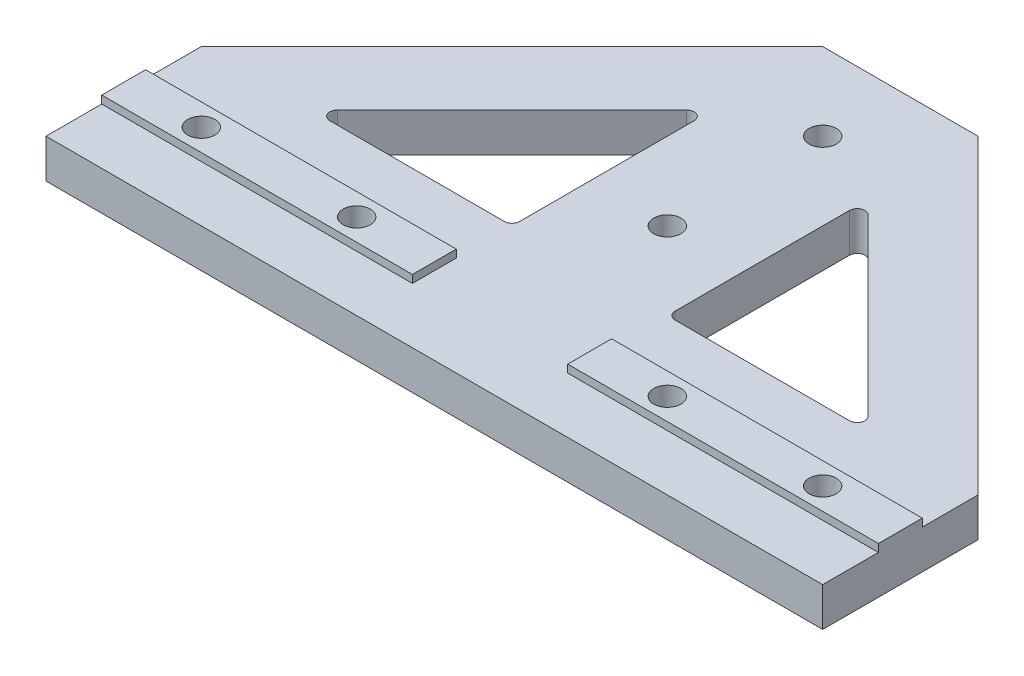
SolidWorks part; units mm, degrees
ref_plane "Plano frontal" through (0, 0, 0) normal (0, 0, 1) x (1, 0, 0)
ref_plane "Plano superior" through (0, 0, 0) normal (0, 1, 0) x (1, 0, 0)
ref_plane "Plano direito" through (0, 0, 0) normal (1, 0, 0) x (0, 0, -1)
sketch "Esboço1" plane through (0, 0, 0) normal (0, 1, 0) x (1, 0, 0)
  line L0 (-50, 0) -> (-50, 20)
  line L1 (-10, 60) -> (10, 60)
  line L2 (10, 60) -> (50, 20)
  line L3 (50, 20) -> (50, 0)
  line L4 (50, 0) -> (-50, 0)
  line L5 (-10, 43.4437) -> (-10, 21)
  line L6 (-33.4437, 20) -> (-11, 20)
  line L7 (-11.7071, 44.1508) -> (-34.1508, 21.7071)
  line L8 (0, 60) -> (0, 0) construction
  line L9 (-50, 10) -> (50, 10) construction
  line L10 (-10, 60) -> (-50, 20)
  line L11 (11.7071, 44.1508) -> (34.1508, 21.7071)
  line L12 (33.4437, 20) -> (11, 20)
  line L13 (10, 43.4437) -> (10, 21)
  arc A0 (-10, 21) -> (-11, 20) centre (-11, 21) cw
  arc A1 (-33.4437, 20) -> (-34.1508, 21.7071) centre (-33.4437, 21) cw
  arc A2 (-11.7071, 44.1508) -> (-10, 43.4437) centre (-11, 43.4437) cw
  circle A3 centre (-40, 10) radius 1.75
  circle A4 centre (-20, 10) radius 1.75
  circle A5 centre (0, 50) radius 1.75
  circle A6 centre (0, 30) radius 1.75
  circle A7 centre (20, 10) radius 1.75
  circle A8 centre (40, 10) radius 1.75
  arc A9 (11.7071, 44.1508) -> (10, 43.4437) centre (11, 43.4437) ccw
  arc A10 (33.4437, 20) -> (34.1508, 21.7071) centre (33.4437, 21) ccw
  arc A11 (10, 21) -> (11, 20) centre (11, 21) ccw
  dimension "D1" = 1
  dimension "D2" = 3.5
  dimension "D3" = 10
  dimension "D4" = 20
  dimension "D5" = 10
  dimension "D6" = 10
  dimension "D7" = 10
  dimension "D8" = 10
  dimension "D9" = 45
  dimension "D10" = 60
  dimension "D11" = 20
  dimension "D12" = 100
  dimension "D13" = 20
extrude "Ressalto-extrusão1" add sketch "Esboço1" along normal blind 5
sketch "Esboço3" plane through (0, 5, 0) normal (0, 1, 0) x (1, 0, 0)
  line L0 (-40, 10) -> (-20, 10) construction
  line L1 (-50, 20) -> (-50, 0) construction
  line L2 (-10, 7.175) -> (-50, 7.175)
  line L3 (-10, 7.175) -> (-10, 12.825)
  line L4 (-10, 12.825) -> (-50, 12.825)
  line L5 (-50, 7.175) -> (-50, 12.825)
  line L6 (-10, 7.175) -> (-50, 12.825) construction
  line L7 (-10, 12.825) -> (-50, 7.175) construction
  line L8 (20, 10) -> (40, 10) construction
  line L9 (50, 0) -> (50, 20) construction
  line L10 (10, 12.825) -> (50, 12.825)
  line L11 (10, 12.825) -> (10, 7.175)
  line L12 (10, 7.175) -> (50, 7.175)
  line L13 (50, 12.825) -> (50, 7.175)
  line L14 (10, 12.825) -> (50, 7.175) construction
  line L15 (10, 7.175) -> (50, 12.825) construction
  point P4 (-30, 10)
  point P17 (30, 10)
  circle M10 centre (40, 10) radius 1.75
  circle M11 centre (20, 10) radius 1.75
  circle M13 centre (-20, 10) radius 1.75
  circle M14 centre (-40, 10) radius 1.75
  line M22 (50, 0) -> (50, 20)
  line M26 (-50, 20) -> (-50, 0)
  dimension "D1" = 5.65
extrude "Ressalto-extrusão2" add sketch "Esboço3" along normal blind 1 contours L3 L4 L2 M26 M13 M14 | L11 L12 L10 M22 M11 M10
